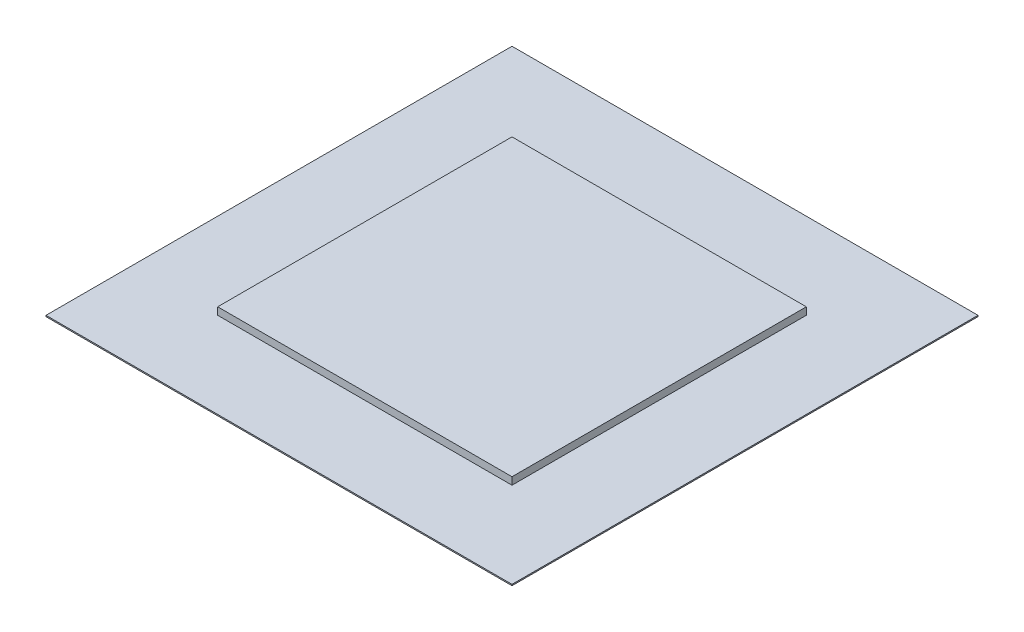
SolidWorks part; units mm, degrees
ref_plane "前视基准面" through (0, 0, 0) normal (0, 0, 1) x (1, 0, 0)
ref_plane "上视基准面" through (0, 0, 0) normal (0, 1, 0) x (1, 0, 0)
ref_plane "右视基准面" through (0, 0, 0) normal (1, 0, 0) x (0, 0, -1)
sketch "草图1" plane through (0, 0, 0) normal (0, 1, 0) x (1, 0, 0)
  line L1 (-1200, 1200) -> (1200, 1200)
  line L2 (-1200, 1200) -> (-1200, -1200)
  line L3 (-1200, -1200) -> (1200, -1200)
  line L4 (1200, 1200) -> (1200, -1200)
  line L5 (-1200, 1200) -> (1200, -1200) construction
  line L6 (-1200, -1200) -> (1200, 1200) construction
  point P0 (0, 0)
  point P6 (0, 0)
  dimension "D1" = 2400
extrude "凸台-拉伸1" add sketch "草图1" along normal blind 60
sketch "草图3" plane through (0, 0, 0) normal (0, -1, 0) x (1, 0, 0)
  line L8 (1900, -1900) -> (1900, 1900)
  line L9 (1900, 1900) -> (-1900, 1900)
  line L10 (-1900, 1900) -> (-1900, -1900)
  line L11 (-1900, -1900) -> (1900, -1900)
  line L12 (1900, -1900) -> (1900, 1900)
  line L13 (1900, 1900) -> (-1900, 1900)
  line L14 (-1900, 1900) -> (-1900, -1900)
  line L15 (-1900, -1900) -> (1900, -1900)
  dimension "D1" = 700
extrude "凸台-拉伸2" add sketch "草图3" along normal blind 10
sketch "草图5" plane through (0, -10, 0) normal (0, -1, 0) x (1, 0, 0)
  line L0 (-1910, 1910) -> (-1910, -1910)
  line L1 (-1910, -1910) -> (1910, -1910)
  line L2 (1910, -1910) -> (1910, 1910)
  line L3 (1910, 1910) -> (-1910, 1910)
  line L4 (-1900, -1900) -> (1900, -1900)
  line L5 (1900, -1900) -> (1900, 1900)
  line L6 (1900, 1900) -> (-1900, 1900)
  line L7 (-1900, 1900) -> (-1900, -1900)
  line L8 (-1900, -1900) -> (1900, -1900)
  line L9 (1900, -1900) -> (1900, 1900)
  line L10 (1900, 1900) -> (-1900, 1900)
  line L11 (-1900, 1900) -> (-1900, -1900)
  dimension "D1" = 0
  dimension "D2" = 10
extrude "凸台-拉伸3" [suppressed] add sketch "草图5" against normal blind 200
